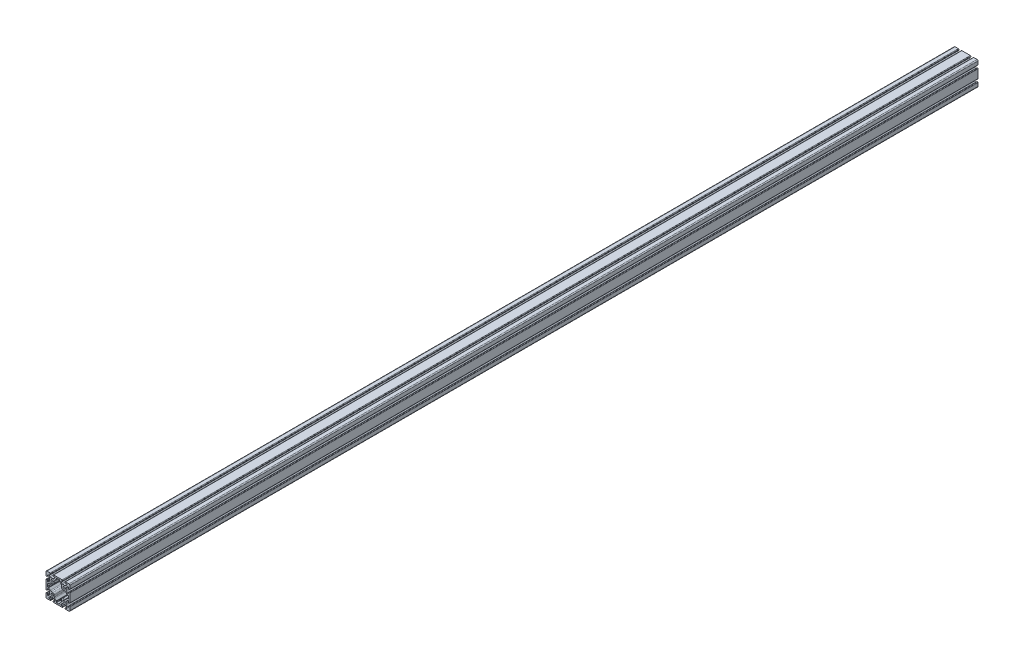
SolidWorks part; units mm, degrees
material "6061 Alloy"
ref_plane "Front Plane" through (0, 0, 0) normal (0, 0, 1) x (1, 0, 0)
ref_plane "Top Plane" through (0, 0, 0) normal (0, 1, 0) x (1, 0, 0)
ref_plane "Right Plane" through (0, 0, 0) normal (1, 0, 0) x (0, 0, -1)
sketch "Sketch1" plane through (0, 0, 0) normal (0, 0, 1) x (1, 0, 0)
  line L0 (0, -40) -> (0, 40) construction
  line L1 (0, 0) -> (-43.5804, 43.5804) construction
  line L2 (-20, 20) -> (-47.7323, 20) construction
  line L3 (-20, 20) -> (3.796, 43.796) construction
  line L4 (-20, 20) -> (-20, 43.5758) construction
  line L5 (-20, -27.7) -> (-20, -47.5576) construction
  line L7 (-36.8718, 24) -> (-28.8718, 24) construction
  line L8 (-36.8718, 24) -> (-36.8718, 16) construction
  line L9 (-36.8718, 16) -> (-28.8718, 16) construction
  line L10 (-28.8718, 24) -> (-28.8718, 16) construction
  line L11 (-36.8718, 24) -> (-28.8718, 16) construction
  line L12 (-36.8718, 16) -> (-28.8718, 24) construction
  line L131 (29.0912, 26.0365) -> (33.0827, 30.028)
  line L132 (27.7, 17.3222) -> (27.7, 22.6778)
  line L133 (29.0912, 13.9635) -> (33.0827, 9.972)
  line L134 (33.6201, 9.7494) -> (34.11, 9.7494)
  line L135 (35.68, 11.3194) -> (35.68, 14.2221)
  line L136 (37.25, 15.7921) -> (38.43, 15.7921)
  line L137 (40, 14.2221) -> (40, 7.0214)
  line L138 (40, 7.0214) -> (40, -7.0214)
  line L139 (40, -7.0214) -> (40, -14.2221)
  line L140 (38.43, -15.7921) -> (37.25, -15.7921)
  line L141 (35.68, -14.2221) -> (35.68, -11.3194)
  line L142 (33.6201, -9.7494) -> (34.11, -9.7494)
  line L143 (29.0912, -13.9635) -> (33.0827, -9.972)
  line L144 (27.7, -22.6778) -> (27.7, -17.3222)
  line L145 (29.0912, -26.0365) -> (33.0827, -30.028)
  line L146 (33.6201, -30.2506) -> (34.11, -30.2506)
  line L147 (35.68, -28.6806) -> (35.68, -25.7779)
  line L148 (37.25, -24.2079) -> (38.43, -24.2079)
  line L149 (40, -25.7779) -> (40, -33.0259)
  line L150 (40, -33.0259) -> (40, -36.83)
  line L151 (36.83, -40) -> (32.9998, -40)
  line L152 (32.9998, -40) -> (25.5696, -40)
  line L153 (23.9996, -38.43) -> (23.9996, -37.25)
  line L154 (25.5696, -35.68) -> (28.4723, -35.68)
  line L155 (30.0413, -34.0552) -> (30.0171, -33.3605)
  line L156 (29.7949, -32.8496) -> (26.0365, -29.0912)
  line L157 (17.3222, -27.7) -> (22.6778, -27.7)
  line L158 (10.035, -33.0197) -> (13.9635, -29.0912)
  line L159 (9.8124, -33.8926) -> (9.8124, -33.5571)
  line L160 (11.3824, -35.4626) -> (14.4246, -35.4626)
  line L161 (15.9946, -37.0326) -> (15.9946, -38.43)
  line L162 (14.4246, -40) -> (6.9987, -40)
  line L163 (6.9987, -40) -> (-6.9987, -40)
  line L164 (-6.9987, -40) -> (-14.4292, -40)
  line L165 (-15.9992, -38.43) -> (-15.9992, -37.25)
  line L166 (-14.4292, -35.68) -> (-11.5265, -35.68)
  line L167 (-9.9574, -34.0552) -> (-9.9816, -33.3618)
  line L168 (-10.2038, -32.8509) -> (-13.9635, -29.0912)
  line L169 (-22.6778, -27.7) -> (-17.3222, -27.7)
  line L170 (-30.028, -33.0827) -> (-26.0365, -29.0912)
  line L171 (-30.2506, -34.11) -> (-30.2506, -33.6201)
  line L172 (-28.6806, -35.68) -> (-25.7231, -35.68)
  line L173 (-24.1531, -37.25) -> (-24.1531, -38.43)
  line L174 (-25.7231, -40) -> (-33, -40)
  line L175 (-33, -40) -> (-36.83, -40)
  line L176 (-40, -36.83) -> (-40, -33.0191)
  line L177 (-40, -33.0191) -> (-40, -25.591)
  line L178 (-38.43, -24.021) -> (-37.25, -24.021)
  line L179 (-35.68, -28.4937) -> (-35.68, -25.591)
  line L180 (-34.0552, -30.0627) -> (-33.3827, -30.0392)
  line L181 (-32.8718, -29.8171) -> (-29.0912, -26.0365)
  line L182 (-27.7, -22.6778) -> (-27.7, -17.3222)
  line L183 (-29.0912, -13.9635) -> (-33.0827, -9.972)
  line L184 (-34.11, -9.7494) -> (-33.6201, -9.7494)
  line L185 (-35.68, -11.3194) -> (-35.68, -14.4473)
  line L186 (-38.43, -16.0173) -> (-37.25, -16.0173)
  line L187 (-40, -14.4473) -> (-40, -7.0169)
  line L188 (-40, -7.0169) -> (-40, 7.0169)
  line L189 (-40, 7.0169) -> (-40, 14.1348)
  line L190 (-38.1948, 15.94) -> (-36.9772, 15.94)
  line L191 (-35.68, 11.3194) -> (-35.68, 14.6428)
  line L192 (-34.11, 9.7494) -> (-33.6201, 9.7494)
  line L193 (-33.0827, 9.972) -> (-29.0912, 13.9635)
  line L194 (-27.7, 17.3222) -> (-27.7, 22.6778)
  line L195 (-29.0912, 26.0365) -> (-33.0827, 30.028)
  line L196 (-34.11, 30.2506) -> (-33.6201, 30.2506)
  line L197 (-35.68, 28.6806) -> (-35.68, 25.3572)
  line L198 (-38.1948, 24.06) -> (-36.9772, 24.06)
  line L199 (-40, 25.8652) -> (-40, 33.3181)
  line L200 (-40, 33.3181) -> (-40, 36.83)
  line L201 (-36.83, 40) -> (-33.0314, 40)
  line L202 (-33.0314, 40) -> (-25.8652, 40)
  line L203 (-24.06, 36.9772) -> (-24.06, 38.1948)
  line L204 (-25.3572, 35.68) -> (-28.7018, 35.68)
  line L205 (-30.285, 33.6069) -> (-30.285, 34.0968)
  line L206 (-30.0961, 33.1508) -> (-26.0365, 29.0912)
  line L207 (-22.6778, 27.7) -> (-17.3222, 27.7)
  line L208 (-13.9635, 29.0912) -> (-9.9039, 33.1508)
  line L209 (-9.715, 33.6069) -> (-9.715, 34.0968)
  line L210 (-14.6428, 35.68) -> (-11.2982, 35.68)
  line L211 (-15.94, 36.9772) -> (-15.94, 38.1948)
  line L212 (-14.1348, 40) -> (-6.9844, 40)
  line L213 (-6.9844, 40) -> (6.9844, 40)
  line L214 (6.9844, 40) -> (14.1348, 40)
  line L215 (15.94, 36.9772) -> (15.94, 38.1948)
  line L216 (14.6428, 35.68) -> (11.2982, 35.68)
  line L217 (9.715, 33.6069) -> (9.715, 34.0968)
  line L218 (9.9039, 33.1508) -> (13.9635, 29.0912)
  line L219 (17.3222, 27.7) -> (22.6778, 27.7)
  line L220 (26.0365, 29.0912) -> (30.028, 33.0827)
  line L221 (30.2506, 33.6201) -> (30.2506, 34.11)
  line L222 (25.5409, 35.679) -> (28.6258, 35.679)
  line L223 (23.9709, 37.249) -> (23.9709, 38.43)
  line L224 (25.5409, 40) -> (36.83, 40)
  line L226 (40, 36.83) -> (40, 32.9339)
  line L227 (40, 32.9339) -> (40, 25.7779)
  line L228 (38.43, 24.2079) -> (37.0956, 24.2079)
  line L229 (35.5256, 25.7779) -> (35.5256, 28.6806)
  line L230 (33.6201, 30.2506) -> (33.9556, 30.2506)
  line L231 (17.07, 12.32) -> (22.6578, 12.32)
  line L232 (26.0165, 10.9288) -> (31.1439, 5.8014)
  line L233 (32.0419, 5.4294) -> (34.41, 5.4294)
  line L234 (35.68, -4.1594) -> (35.68, 4.1594)
  line L235 (32.0419, -5.4294) -> (34.41, -5.4294)
  line L236 (26.0165, -10.9288) -> (31.1439, -5.8014)
  line L237 (17.07, -12.32) -> (22.6578, -12.32)
  line L238 (12.32, -22.6578) -> (12.32, -17.07)
  line L239 (5.8014, -31.1439) -> (10.9288, -26.0165)
  line L240 (5.4294, -34.41) -> (5.4294, -32.0419)
  line L241 (-4.1594, -35.68) -> (4.1594, -35.68)
  line L242 (-5.4294, -34.41) -> (-5.4294, -32.0419)
  line L243 (-5.8014, -31.1439) -> (-10.9288, -26.0165)
  line L244 (-12.32, -22.6578) -> (-12.32, -17.07)
  line L245 (-22.6578, -12.32) -> (-17.07, -12.32)
  line L246 (-26.0165, -10.9288) -> (-31.1439, -5.8014)
  line L247 (-34.41, -5.4294) -> (-32.0419, -5.4294)
  line L248 (-35.68, -4.1594) -> (-35.68, 4.1594)
  line L249 (-34.41, 5.4294) -> (-32.0419, 5.4294)
  line L250 (-31.1439, 5.8014) -> (-26.0165, 10.9288)
  line L251 (-22.6578, 12.32) -> (-17.07, 12.32)
  line L252 (-12.32, 17.07) -> (-12.32, 22.6578)
  line L253 (-10.9288, 26.0165) -> (-5.8014, 31.1439)
  line L254 (-5.4294, 32.0419) -> (-5.4294, 34.41)
  line L255 (-4.1594, 35.68) -> (4.1594, 35.68)
  line L256 (5.4294, 32.0419) -> (5.4294, 34.41)
  line L257 (5.8014, 31.1439) -> (10.9288, 26.0165)
  line L258 (12.32, 17.07) -> (12.32, 22.6578)
  line L260 (-40, 0) -> (40, 0) construction
  circle A0 centre (-32.8718, 20) radius 4 construction
  circle A116 centre (-20, 20) radius 3.4
  circle A117 centre (20, 20) radius 3.4
  circle A118 centre (20, -20) radius 3.4
  circle A119 centre (-20, -20) radius 3.4
  arc A120 (29.0912, 26.0365) -> (27.7, 22.6778) centre (32.45, 22.6778) ccw
  arc A121 (27.7, 17.3222) -> (29.0912, 13.9635) centre (32.45, 17.3222) ccw
  arc A122 (33.0827, 9.972) -> (33.6201, 9.7494) centre (33.6201, 10.5094) ccw
  arc A123 (34.11, 9.7494) -> (35.68, 11.3194) centre (34.11, 11.3194) ccw
  arc A124 (37.25, 15.7921) -> (35.68, 14.2221) centre (37.25, 14.2221) ccw
  arc A125 (40, 14.2221) -> (38.43, 15.7921) centre (38.43, 14.2221) ccw
  arc A126 (38.43, -15.7921) -> (40, -14.2221) centre (38.43, -14.2221) ccw
  arc A127 (35.68, -14.2221) -> (37.25, -15.7921) centre (37.25, -14.2221) ccw
  arc A128 (35.68, -11.3194) -> (34.11, -9.7494) centre (34.11, -11.3194) ccw
  arc A129 (33.6201, -9.7494) -> (33.0827, -9.972) centre (33.6201, -10.5094) ccw
  arc A130 (29.0912, -13.9635) -> (27.7, -17.3222) centre (32.45, -17.3222) ccw
  arc A131 (27.7, -22.6778) -> (29.0912, -26.0365) centre (32.45, -22.6778) ccw
  arc A132 (33.0827, -30.028) -> (33.6201, -30.2506) centre (33.6201, -29.4906) ccw
  arc A133 (34.11, -30.2506) -> (35.68, -28.6806) centre (34.11, -28.6806) ccw
  arc A134 (37.25, -24.2079) -> (35.68, -25.7779) centre (37.25, -25.7779) ccw
  arc A135 (40, -25.7779) -> (38.43, -24.2079) centre (38.43, -25.7779) ccw
  arc A136 (36.83, -40) -> (40, -36.83) centre (36.83, -36.83) ccw
  arc A137 (23.9996, -38.43) -> (25.5696, -40) centre (25.5696, -38.43) ccw
  arc A138 (25.5696, -35.68) -> (23.9996, -37.25) centre (25.5696, -37.25) ccw
  arc A139 (28.4723, -35.68) -> (30.0413, -34.0552) centre (28.4723, -34.11) ccw
  arc A140 (30.0171, -33.3605) -> (29.7949, -32.8496) centre (29.2575, -33.387) ccw
  arc A141 (26.0365, -29.0912) -> (22.6778, -27.7) centre (22.6778, -32.45) ccw
  arc A142 (17.3222, -27.7) -> (13.9635, -29.0912) centre (17.3222, -32.45) ccw
  arc A143 (10.035, -33.0197) -> (9.8124, -33.5571) centre (10.5724, -33.5571) ccw
  arc A144 (9.8124, -33.8926) -> (11.3824, -35.4626) centre (11.3824, -33.8926) ccw
  arc A145 (15.9946, -37.0326) -> (14.4246, -35.4626) centre (14.4246, -37.0326) ccw
  arc A146 (14.4246, -40) -> (15.9946, -38.43) centre (14.4246, -38.43) ccw
  arc A147 (-15.9992, -38.43) -> (-14.4292, -40) centre (-14.4292, -38.43) ccw
  arc A148 (-14.4292, -35.68) -> (-15.9992, -37.25) centre (-14.4292, -37.25) ccw
  arc A149 (-11.5265, -35.68) -> (-9.9574, -34.0552) centre (-11.5265, -34.11) ccw
  arc A150 (-9.9816, -33.3618) -> (-10.2038, -32.8509) centre (-10.7412, -33.3883) ccw
  arc A151 (-13.9635, -29.0912) -> (-17.3222, -27.7) centre (-17.3222, -32.45) ccw
  arc A152 (-22.6778, -27.7) -> (-26.0365, -29.0912) centre (-22.6778, -32.45) ccw
  arc A153 (-30.028, -33.0827) -> (-30.2506, -33.6201) centre (-29.4906, -33.6201) ccw
  arc A154 (-30.2506, -34.11) -> (-28.6806, -35.68) centre (-28.6806, -34.11) ccw
  arc A155 (-24.1531, -37.25) -> (-25.7231, -35.68) centre (-25.7231, -37.25) ccw
  arc A156 (-25.7231, -40) -> (-24.1531, -38.43) centre (-25.7231, -38.43) ccw
  arc A157 (-40, -36.83) -> (-36.83, -40) centre (-36.83, -36.83) ccw
  arc A158 (-38.43, -24.021) -> (-40, -25.591) centre (-38.43, -25.591) ccw
  arc A159 (-35.68, -25.591) -> (-37.25, -24.021) centre (-37.25, -25.591) ccw
  arc A160 (-35.68, -28.4937) -> (-34.0552, -30.0627) centre (-34.11, -28.4937) ccw
  arc A161 (-33.3827, -30.0392) -> (-32.8718, -29.8171) centre (-33.4092, -29.2797) ccw
  arc A162 (-29.0912, -26.0365) -> (-27.7, -22.6778) centre (-32.45, -22.6778) ccw
  arc A163 (-27.7, -17.3222) -> (-29.0912, -13.9635) centre (-32.45, -17.3222) ccw
  arc A164 (-33.0827, -9.972) -> (-33.6201, -9.7494) centre (-33.6201, -10.5094) ccw
  arc A165 (-34.11, -9.7494) -> (-35.68, -11.3194) centre (-34.11, -11.3194) ccw
  arc A166 (-37.25, -16.0173) -> (-35.68, -14.4473) centre (-37.25, -14.4473) ccw
  arc A167 (-40, -14.4473) -> (-38.43, -16.0173) centre (-38.43, -14.4473) ccw
  arc A168 (-38.1948, 15.94) -> (-40, 14.1348) centre (-38.1948, 14.1348) ccw
  arc A169 (-35.68, 14.6428) -> (-36.9772, 15.94) centre (-36.9772, 14.6428) ccw
  arc A170 (-35.68, 11.3194) -> (-34.11, 9.7494) centre (-34.11, 11.3194) ccw
  arc A171 (-33.6201, 9.7494) -> (-33.0827, 9.972) centre (-33.6201, 10.5094) ccw
  arc A172 (-29.0912, 13.9635) -> (-27.7, 17.3222) centre (-32.45, 17.3222) ccw
  arc A173 (-27.7, 22.6778) -> (-29.0912, 26.0365) centre (-32.45, 22.6778) ccw
  arc A174 (-33.0827, 30.028) -> (-33.6201, 30.2506) centre (-33.6201, 29.4906) ccw
  arc A175 (-34.11, 30.2506) -> (-35.68, 28.6806) centre (-34.11, 28.6806) ccw
  arc A176 (-36.9772, 24.06) -> (-35.68, 25.3572) centre (-36.9772, 25.3572) ccw
  arc A177 (-40, 25.8652) -> (-38.1948, 24.06) centre (-38.1948, 25.8652) ccw
  arc A178 (-36.83, 40) -> (-40, 36.83) centre (-36.83, 36.83) ccw
  arc A179 (-24.06, 38.1948) -> (-25.8652, 40) centre (-25.8652, 38.1948) ccw
  arc A180 (-25.3572, 35.68) -> (-24.06, 36.9772) centre (-25.3572, 36.9772) ccw
  arc A181 (-28.7018, 35.68) -> (-30.285, 34.0968) centre (-28.7018, 34.0968) ccw
  arc A182 (-30.285, 33.6069) -> (-30.0961, 33.1508) centre (-29.6399, 33.6069) ccw
  arc A183 (-26.0365, 29.0912) -> (-22.6778, 27.7) centre (-22.6778, 32.45) ccw
  arc A184 (-17.3222, 27.7) -> (-13.9635, 29.0912) centre (-17.3222, 32.45) ccw
  arc A185 (-9.9039, 33.1508) -> (-9.715, 33.6069) centre (-10.3601, 33.6069) ccw
  arc A186 (-9.715, 34.0968) -> (-11.2982, 35.68) centre (-11.2982, 34.0968) ccw
  arc A187 (-15.94, 36.9772) -> (-14.6428, 35.68) centre (-14.6428, 36.9772) ccw
  arc A188 (-14.1348, 40) -> (-15.94, 38.1948) centre (-14.1348, 38.1948) ccw
  arc A189 (15.94, 38.1948) -> (14.1348, 40) centre (14.1348, 38.1948) ccw
  arc A190 (14.6428, 35.68) -> (15.94, 36.9772) centre (14.6428, 36.9772) ccw
  arc A191 (11.2982, 35.68) -> (9.715, 34.0968) centre (11.2982, 34.0968) ccw
  arc A192 (9.715, 33.6069) -> (9.9039, 33.1508) centre (10.3601, 33.6069) ccw
  arc A193 (13.9635, 29.0912) -> (17.3222, 27.7) centre (17.3222, 32.45) ccw
  arc A194 (22.6778, 27.7) -> (26.0365, 29.0912) centre (22.6778, 32.45) ccw
  arc A195 (30.028, 33.0827) -> (30.2506, 33.6201) centre (29.4906, 33.6201) ccw
  arc A196 (30.2506, 34.11) -> (28.6258, 35.679) centre (28.6806, 34.11) ccw
  arc A197 (23.9709, 37.249) -> (25.5409, 35.679) centre (25.5409, 37.249) ccw
  arc A198 (25.5409, 40) -> (23.9709, 38.43) centre (25.5409, 38.43) ccw
  arc A199 (40, 36.83) -> (36.83, 40) centre (36.83, 36.83) ccw
  arc A200 (38.43, 24.2079) -> (40, 25.7779) centre (38.43, 25.7779) ccw
  arc A201 (35.5256, 25.7779) -> (37.0956, 24.2079) centre (37.0956, 25.7779) ccw
  arc A202 (35.5256, 28.6806) -> (33.9556, 30.2506) centre (33.9556, 28.6806) ccw
  arc A203 (33.6201, 30.2506) -> (33.0827, 30.028) centre (33.6201, 29.4906) ccw
  arc A204 (26.0165, 10.9288) -> (22.6578, 12.32) centre (22.6578, 7.57) ccw
  arc A205 (31.1439, 5.8014) -> (32.0419, 5.4294) centre (32.0419, 6.6994) ccw
  arc A206 (35.68, 4.1594) -> (34.41, 5.4294) centre (34.41, 4.1594) ccw
  arc A207 (34.41, -5.4294) -> (35.68, -4.1594) centre (34.41, -4.1594) ccw
  arc A208 (32.0419, -5.4294) -> (31.1439, -5.8014) centre (32.0419, -6.6994) ccw
  arc A209 (22.6578, -12.32) -> (26.0165, -10.9288) centre (22.6578, -7.57) ccw
  arc A210 (17.07, -12.32) -> (12.32, -17.07) centre (17.07, -17.07) ccw
  arc A211 (10.9288, -26.0165) -> (12.32, -22.6578) centre (7.57, -22.6578) ccw
  arc A212 (5.8014, -31.1439) -> (5.4294, -32.0419) centre (6.6994, -32.0419) ccw
  arc A213 (4.1594, -35.68) -> (5.4294, -34.41) centre (4.1594, -34.41) ccw
  arc A214 (-5.4294, -34.41) -> (-4.1594, -35.68) centre (-4.1594, -34.41) ccw
  arc A215 (-5.4294, -32.0419) -> (-5.8014, -31.1439) centre (-6.6994, -32.0419) ccw
  arc A216 (-12.32, -22.6578) -> (-10.9288, -26.0165) centre (-7.57, -22.6578) ccw
  arc A217 (-12.32, -17.07) -> (-17.07, -12.32) centre (-17.07, -17.07) ccw
  arc A218 (-26.0165, -10.9288) -> (-22.6578, -12.32) centre (-22.6578, -7.57) ccw
  arc A219 (-31.1439, -5.8014) -> (-32.0419, -5.4294) centre (-32.0419, -6.6994) ccw
  arc A220 (-35.68, -4.1594) -> (-34.41, -5.4294) centre (-34.41, -4.1594) ccw
  arc A221 (-34.41, 5.4294) -> (-35.68, 4.1594) centre (-34.41, 4.1594) ccw
  arc A222 (-32.0419, 5.4294) -> (-31.1439, 5.8014) centre (-32.0419, 6.6994) ccw
  arc A223 (-22.6578, 12.32) -> (-26.0165, 10.9288) centre (-22.6578, 7.57) ccw
  arc A224 (-17.07, 12.32) -> (-12.32, 17.07) centre (-17.07, 17.07) ccw
  arc A225 (-10.9288, 26.0165) -> (-12.32, 22.6578) centre (-7.57, 22.6578) ccw
  arc A226 (-5.8014, 31.1439) -> (-5.4294, 32.0419) centre (-6.6994, 32.0419) ccw
  arc A227 (-4.1594, 35.68) -> (-5.4294, 34.41) centre (-4.1594, 34.41) ccw
  arc A228 (5.4294, 34.41) -> (4.1594, 35.68) centre (4.1594, 34.41) ccw
  arc A229 (5.4294, 32.0419) -> (5.8014, 31.1439) centre (6.6994, 32.0419) ccw
  arc A230 (12.32, 22.6578) -> (10.9288, 26.0165) centre (7.57, 22.6578) ccw
  arc A231 (12.32, 17.07) -> (17.07, 12.32) centre (17.07, 17.07) ccw
  point P9 (-32.8718, 20)
  dimension "D8" = 6.8
  dimension "D1" = 80
  dimension "D2" = 40
  dimension "D3" = 20
  dimension "D4" = 20.57
  dimension "D5" = 4.32
  dimension "D6" = 4.32
  dimension "D7" = 8.12
  dimension "D9" = 4.32
  dimension "D10" = 12.3
  dimension "D11" = 8
  dimension "D12" = 8
extrude "Extrude1" add sketch "Sketch1" against normal blind 3048
